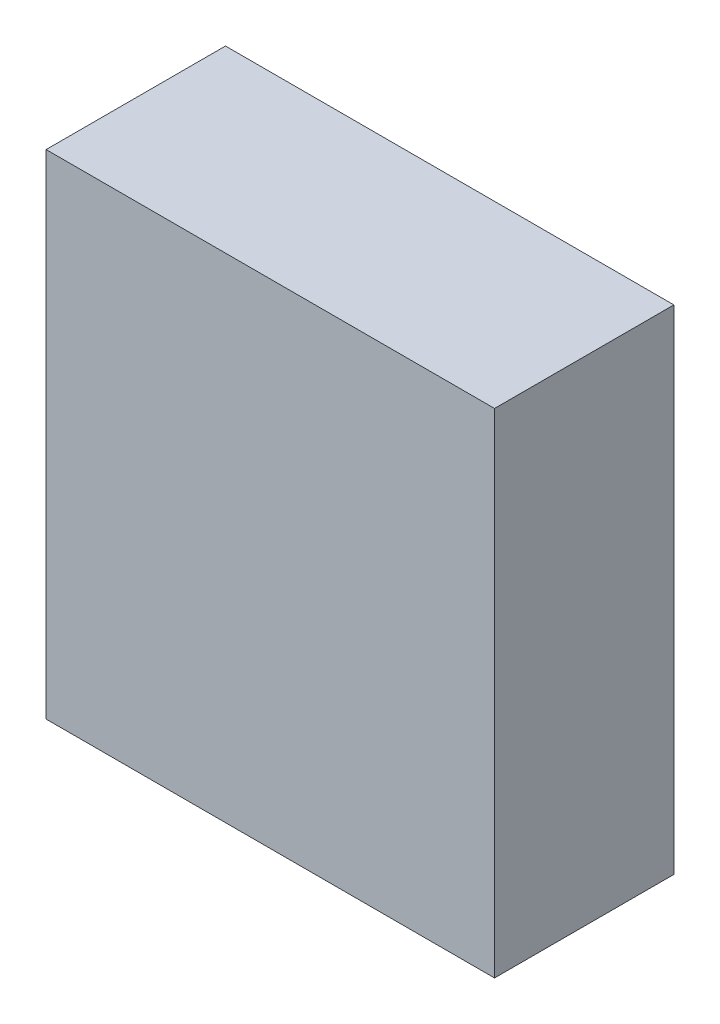
SolidWorks part; units mm, degrees
ref_plane "Front Plane" through (0, 0, 0) normal (0, 0, 1) x (1, 0, 0)
ref_plane "Top Plane" through (0, 0, 0) normal (0, 1, 0) x (1, 0, 0)
ref_plane "Right Plane" through (0, 0, 0) normal (1, 0, 0) x (0, 0, -1)
sketch "Sketch1" plane through (0, 0, 0) normal (0, 1, 0) x (1, 0, 0)
  line L1 (0, 0) -> (250, 0)
  line L2 (0, 0) -> (0, 100)
  line L3 (0, 100) -> (250, 100)
  line L4 (250, 0) -> (250, 100)
  line L5 (0, 0) -> (250, 100) construction
  line L6 (0, 100) -> (250, 0) construction
  point P4 (125, 50)
  dimension "D1" = 100
  dimension "D2" = 250
extrude "Boss-Extrude1" add sketch "Sketch1" along normal blind 275
